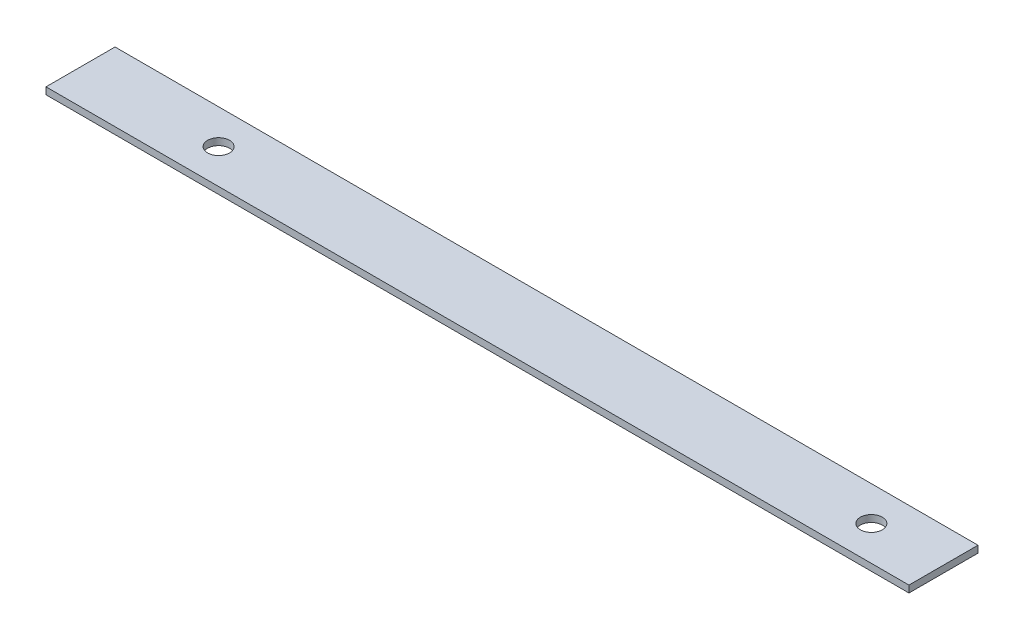
SolidWorks part; units mm, degrees
ref_plane "Front Plane" through (0, 0, 0) normal (0, 0, 1) x (1, 0, 0)
ref_plane "Top Plane" through (0, 0, 0) normal (0, 1, 0) x (1, 0, 0)
ref_plane "Right Plane" through (0, 0, 0) normal (1, 0, 0) x (0, 0, -1)
sketch "Sketch1" plane through (0, 0, 0) normal (0, 1, 0) x (1, 0, 0)
  line L6 (175.391, 11.6562) -> (-74.609, 11.6562)
  line L7 (-74.609, 11.6562) -> (-74.609, -8.3438)
  line L8 (-74.609, -8.3438) -> (175.391, -8.3438)
  line L10 (175.391, 11.6562) -> (175.391, -8.3438)
  dimension "D1" = 250
  dimension "D2" = 20
extrude "Boss-Extrude1" add sketch "Sketch1" along normal blind 2
sketch "Sketch5" plane through (0, 0, 0) normal (0, -1, 0) x (1, 0, 0)
  line L0 (-74.609, -1.6562) -> (175.391, -1.6562)
  line L1 (-74.609, -11.6562) -> (-74.609, 8.3438) construction
  line L2 (175.391, 8.3438) -> (175.391, -11.6562) construction
  line L3 (-52.609, -1.6562) -> (-52.609, -26.6562)
  point P6 (154.492, -1.6562)
  point P7 (-34.609, -1.6562)
  point P8 (-52.609, -1.6562)
  dimension "D1" = 189.101
  dimension "D2" = 22
  dimension "D3" = 40
  dimension "D4" = 25
sketch "Sketch6" plane through (0, 0, 0) normal (0, -1, 0) x (1, 0, 0)
  circle A0 centre (-34.609, -1.6562) radius 3.175
  circle A1 centre (154.492, -1.6562) radius 3.175
  dimension "D1" = 6.35
extrude "Cut-Extrude1" cut sketch "Sketch6" against normal through all
